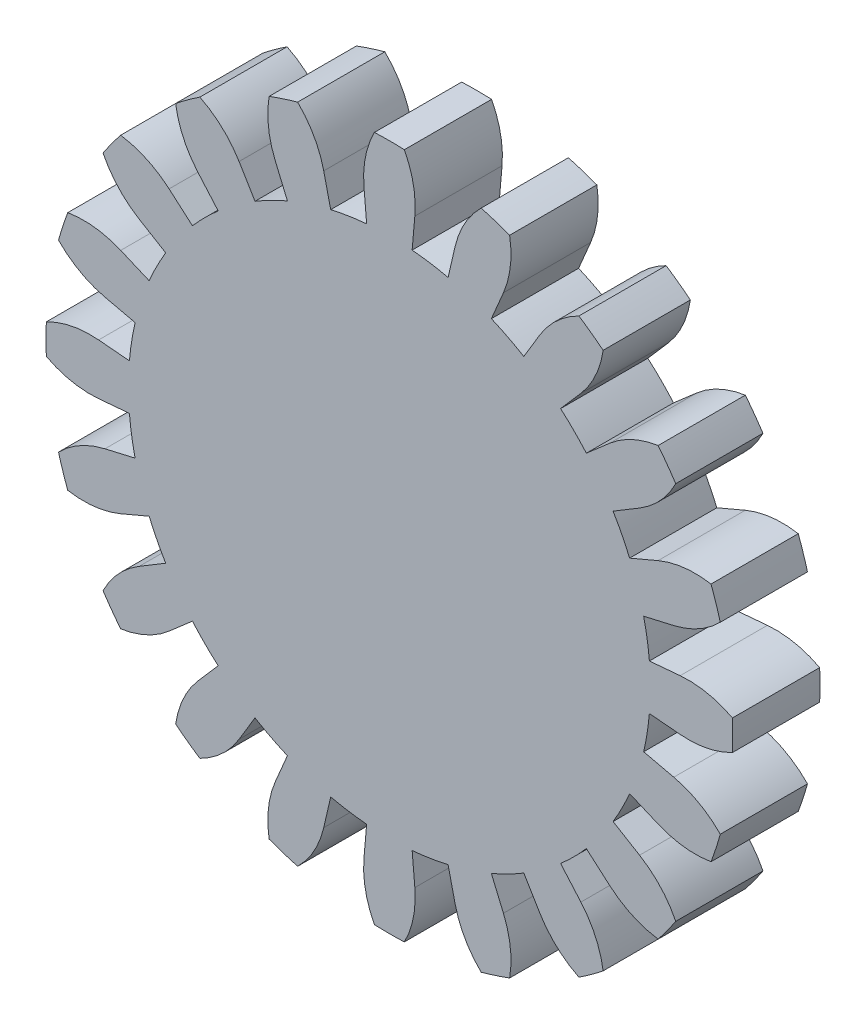
SolidWorks part; units mm, degrees
ref_plane "Front Plane" through (0, 0, 0) normal (0, 0, 1) x (1, 0, 0)
ref_plane "Top Plane" through (0, 0, 0) normal (0, 1, 0) x (1, 0, 0)
ref_plane "Right Plane" through (0, 0, 0) normal (1, 0, 0) x (0, 0, -1)
sketch "Sketch4" plane through (0, 0, 0) normal (0, 0, 1) x (1, 0, 0)
  line L0 (0, 0) -> (70.055, 0) construction
  line L1 (0, 0) -> (57.3139, 2.5024) construction
  line L2 (0, 0) -> (61.7902, 5.4059) construction
  line L3 (0, 0) -> (70.6997, 12.4663) construction
  line L4 (21.1691, 1.8521) -> (18.9277, 1.656)
  line L5 (0, 0) -> (18.7113, 3.2993)
  line L6 (21.1691, -1.8521) -> (18.9277, -1.656)
  line L7 (0, 0) -> (18.7113, -3.2993)
  arc A0 (24.9762, -1.0905) -> (24.9762, 1.0905) centre (0, 0) ccw
  circle A1 centre (0, 0) radius 21.25 construction
  arc A3 (21.1691, 1.8521) -> (24.9762, 1.0905) centre (21.7715, -5.0331) cw
  arc A5 (18.9277, 1.656) -> (18.7113, 3.2993) centre (0, 0) ccw construction
  arc A6 (18.9277, 1.656) -> (18.7113, 3.2993) centre (0, 0) ccw
  arc A7 (21.1691, -1.8521) -> (24.9762, -1.0905) centre (21.7715, 5.0331) ccw
  arc A8 (18.9277, -1.656) -> (18.7113, -3.2993) centre (0, 0) cw
  dimension "D1" = 19
  dimension "D2" = 42.5
  dimension "D3" = 50
  dimension "D4" = 2.5
  dimension "D5" = 5
  dimension "D6" = 10
extrude "Boss-Extrude2" add sketch "Sketch4" along normal blind 6.35
pattern_circular "CirPattern1" count 20 over 360 about axis through (0, 0, 0) along (0, 0, 1) of "Boss-Extrude2"
